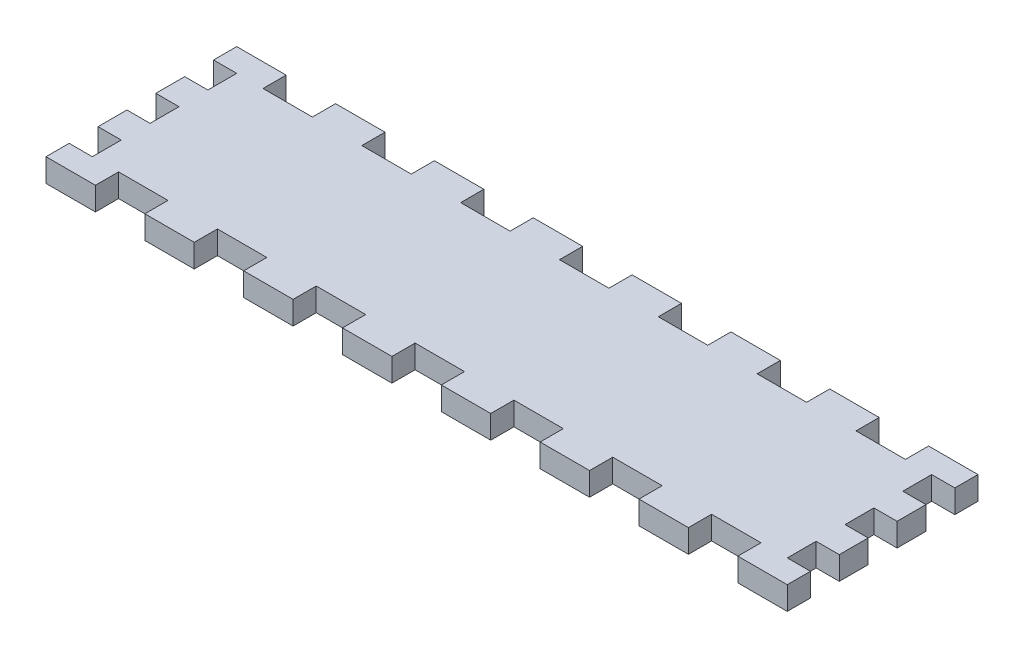
SolidWorks part; units mm, degrees
ref_plane "Front Plane" through (0, 0, 0) normal (0, 0, 1) x (1, 0, 0)
ref_plane "Top Plane" through (0, 0, 0) normal (0, 1, 0) x (1, 0, 0)
ref_plane "Right Plane" through (0, 0, 0) normal (1, 0, 0) x (0, 0, -1)
sketch "Sketch1" plane through (0, 0, 0) normal (0, 1, 0) x (1, 0, 0)
  line L0 (-61.9082, -12.6565) -> (-61.9082, -20.5741)
  line L1 (-61.9082, 17.4462) -> (-48.3615, 17.4462)
  line L2 (-61.9082, 17.4462) -> (-61.9082, 11.0962)
  line L3 (-61.9082, -34.8416) -> (-48.3615, -34.8416)
  line L4 (141.2918, 17.4462) -> (141.2918, 11.0962)
  line L5 (-61.9082, 11.0962) -> (-55.5582, 11.0962)
  line L6 (-61.9082, -28.4916) -> (-61.9082, -34.8416)
  line L7 (-61.9082, -12.6565) -> (-55.5582, -12.6565)
  line L8 (-55.5582, 11.0962) -> (-55.5582, 3.1787)
  line L9 (-61.9082, -20.5741) -> (-55.5582, -20.5741)
  line L10 (141.2918, -12.6565) -> (141.2918, -20.5741)
  line L11 (-61.9082, -28.4916) -> (-55.5582, -28.4916)
  line L12 (-55.5582, -20.5741) -> (-55.5582, -28.4916)
  line L13 (141.2918, 11.0962) -> (134.9418, 11.0962)
  line L14 (141.2918, -28.4916) -> (141.2918, -34.8416)
  line L15 (141.2918, -12.6565) -> (134.9418, -12.6565)
  line L16 (134.9418, 11.0962) -> (134.9418, 3.1787)
  line L17 (141.2918, -20.5741) -> (134.9418, -20.5741)
  line L18 (-55.5582, -4.7389) -> (-55.5582, -12.6565)
  line L19 (141.2918, -28.4916) -> (134.9418, -28.4916)
  line L20 (134.9418, -20.5741) -> (134.9418, -28.4916)
  line L21 (-7.7215, 17.4462) -> (5.8252, 17.4462)
  line L22 (-28.0415, 17.4462) -> (-28.0417, -34.8416) construction
  line L23 (-55.5582, -4.7389) -> (-61.9082, -4.7389)
  line L24 (134.9418, -4.7389) -> (134.9418, -12.6565)
  line L25 (19.3718, 17.4462) -> (32.9185, 17.4462)
  line L26 (-21.2682, 17.4462) -> (-21.2682, 11.0962)
  line L27 (-21.2682, 11.0962) -> (-7.7215, 11.0962)
  line L28 (-7.7215, 17.4462) -> (-7.7215, 11.0962)
  line L29 (46.4652, 17.4462) -> (60.0118, 17.4462)
  line L30 (5.8252, 17.4462) -> (5.8252, 11.0962)
  line L31 (5.8252, 11.0962) -> (19.3718, 11.0962)
  line L32 (19.3718, 17.4462) -> (19.3718, 11.0962)
  line L33 (73.5585, 17.4462) -> (87.1052, 17.4462)
  line L34 (32.9185, 17.4462) -> (32.9185, 11.0962)
  line L35 (32.9185, 11.0962) -> (46.4652, 11.0962)
  line L36 (46.4652, 17.4462) -> (46.4652, 11.0962)
  line L37 (-55.5582, 3.1787) -> (-61.9082, 3.1787)
  line L38 (60.0118, 17.4462) -> (60.0118, 11.0962)
  line L39 (60.0118, 11.0962) -> (73.5585, 11.0962)
  line L40 (73.5585, 17.4462) -> (73.5585, 11.0962)
  line L41 (100.6519, 17.4462) -> (114.1985, 17.4462)
  line L42 (87.1052, 17.4462) -> (87.1052, 11.0962)
  line L43 (87.1052, 11.0962) -> (100.6519, 11.0962)
  line L44 (-61.9082, -4.7389) -> (-61.9082, 3.1787)
  line L45 (127.7452, 17.4462) -> (141.2918, 17.4462)
  line L46 (134.9418, 3.1787) -> (141.2918, 3.1787)
  line L48 (100.6519, 17.4462) -> (100.6519, 11.0962)
  line L49 (127.7435, -34.8416) -> (141.2918, -34.8416)
  line L50 (114.1985, 17.4462) -> (114.1985, 11.0962)
  line L51 (114.1985, 11.0962) -> (127.7452, 11.0962)
  line L52 (127.7452, 17.4462) -> (127.7452, 11.0962)
  line L53 (-34.8148, 17.4462) -> (-21.2682, 17.4462)
  line L54 (-48.3615, 17.4462) -> (-48.3615, 11.0962)
  line L55 (-48.3615, 11.0962) -> (-34.8148, 11.0962)
  line L56 (-34.8148, 17.4462) -> (-34.8148, 11.0962)
  line L57 (134.9418, -4.7389) -> (141.2918, -4.7389)
  line L58 (-48.3615, -34.8416) -> (-48.3615, -28.4916)
  line L59 (-48.3615, -28.4916) -> (-34.8148, -28.4916)
  line L60 (141.2918, 3.1787) -> (141.2918, -4.7389)
  line L64 (-34.8148, -34.8416) -> (-34.8148, -28.4916)
  line L65 (-34.8148, -34.8416) -> (-21.2687, -34.8416)
  line L66 (-21.2687, -34.8416) -> (-21.2687, -28.4916)
  line L67 (-21.2687, -28.4916) -> (-7.7225, -28.4916)
  line L68 (-7.7225, -34.8416) -> (-7.7225, -28.4916)
  line L69 (-7.7225, -34.8416) -> (5.8237, -34.8416)
  line L70 (5.8237, -34.8416) -> (5.8237, -28.4916)
  line L71 (5.8237, -28.4916) -> (19.3698, -28.4916)
  line L72 (19.3698, -34.8416) -> (19.3698, -28.4916)
  line L73 (19.3698, -34.8416) -> (32.916, -34.8416)
  line L74 (32.916, -34.8416) -> (32.916, -28.4916)
  line L75 (32.916, -28.4916) -> (46.4622, -28.4916)
  line L76 (46.4622, -34.8416) -> (46.4622, -28.4916)
  line L77 (46.4622, -34.8416) -> (60.0083, -34.8416)
  line L78 (60.0083, -34.8416) -> (60.0083, -28.4916)
  line L79 (60.0083, -28.4916) -> (73.5545, -28.4916)
  line L80 (73.5545, -34.8416) -> (73.5545, -28.4916)
  line L81 (73.5545, -34.8416) -> (87.1006, -34.8416)
  line L82 (87.1006, -34.8416) -> (87.1006, -28.4916)
  line L83 (87.1006, -28.4916) -> (100.6468, -28.4916)
  line L88 (100.6468, -34.8416) -> (100.6468, -28.4916)
  line L89 (100.6468, -34.8416) -> (114.1952, -34.8416)
  line L90 (114.1952, -34.8416) -> (114.1952, -28.4916)
  line L91 (114.1952, -28.4916) -> (127.7435, -28.4916)
  line L92 (127.7435, -34.8416) -> (127.7435, -28.4916)
extrude "Boss-Extrude1" add sketch "Sketch1" along normal blind 6.35
